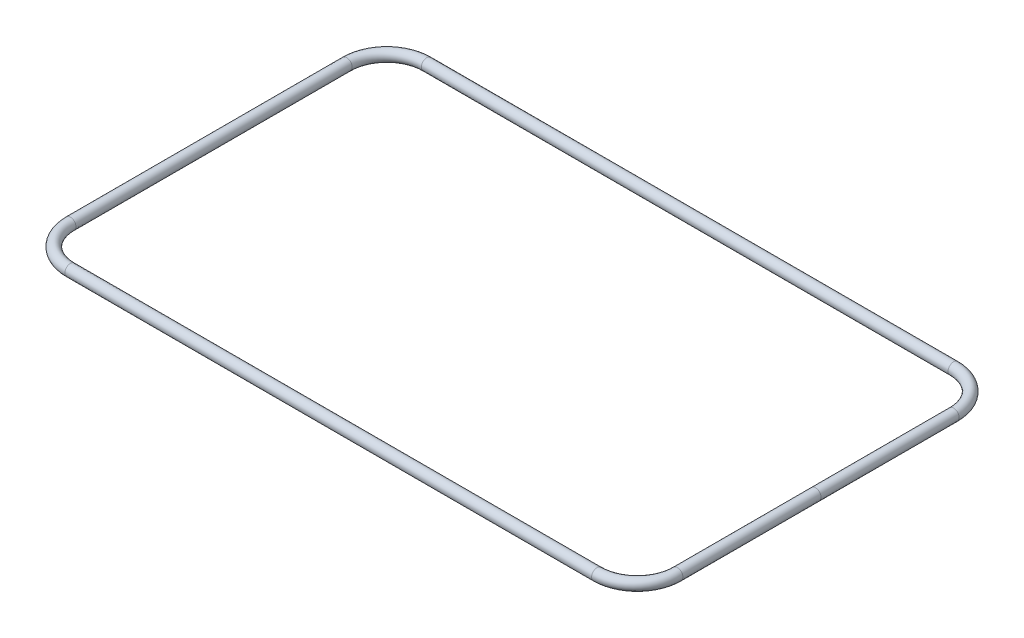
SolidWorks part; units mm, degrees
ref_plane "Front Plane" through (0, 0, 0) normal (0, 0, 1) x (1, 0, 0)
ref_plane "Top Plane" through (0, 0, 0) normal (0, 1, 0) x (1, 0, 0)
ref_plane "Right Plane" through (0, 0, 0) normal (1, 0, 0) x (0, 0, -1)
sketch "BaseDimensions" plane through (0, 0, 0) normal (0, 1, 0) x (1, 0, 0)
  line L0 (0, -63.5) -> (0, 63.5) construction
  line L1 (101.6, 0) -> (-101.6, 0) construction
  point P5 (0, 0)
  point P6 (0, 0)
  dimension "D1" = 127
  dimension "D2" = 203.2
sketch "O-RingPath" plane through (0, 0, 0) normal (0, 1, 0) x (1, 0, 0)
  line L0 (83.3968, -56.4388) -> (-83.3968, -56.4388)
  line L1 (96.0968, -43.7388) -> (96.0968, 43.7388)
  line L2 (0, 0) -> (0, -56.4388) construction
  line L3 (96.0968, 0) -> (0, 0) construction
  line L4 (-96.0968, -43.7388) -> (-96.0968, 43.7388)
  line L5 (83.3968, 56.4388) -> (-83.3968, 56.4388)
  arc A0 (83.3968, -56.4388) -> (96.0968, -43.7388) centre (83.3968, -43.7388) ccw
  arc A1 (-83.3968, -56.4388) -> (-96.0968, -43.7388) centre (-83.3968, -43.7388) cw
  arc A2 (-83.3968, 56.4388) -> (-96.0968, 43.7388) centre (-83.3968, 43.7388) ccw
  arc A3 (83.3968, 56.4388) -> (96.0968, 43.7388) centre (83.3968, 43.7388) cw
  point P17 (-96.0968, 0)
  dimension "D2" = 12.7
  dimension "D3" = 7.0612
sketch "O-RingProfile" plane through (0, 0, 0) normal (0, 0, 1) x (1, 0, 0)
  circle A0 centre (96.0968, 0) radius 1.7653
  dimension "D1" = 3.5306
sweep "Sweep2" add profiles "O-RingProfile" path "O-RingPath"
ref_plane "TopOfRing" through (0, 1.7653, 0) normal (0, 1, 0) x (1, 0, 0)
ref_plane "BottomOfRing" through (0, -1.7653, 0) normal (0, -1, 0) x (-1, 0, 0)
equation "\"D1@O-RingProfile\" = \"O-Ring_CS@BladderAssembly.Assembly\""
equation "\"D1@BaseDimensions\"=\"BaseWidth@BladderAssembly.Assembly\""
equation "\"D2@BaseDimensions\"=\"BaseLength@BladderAssembly.Assembly\""
equation "\"O_Ring_Len\"= \"O-Ring_Len@BladderAssembly.Assembly\""
equation "\"D1@O-RingPath\"=\"O_Ring_Len\""
